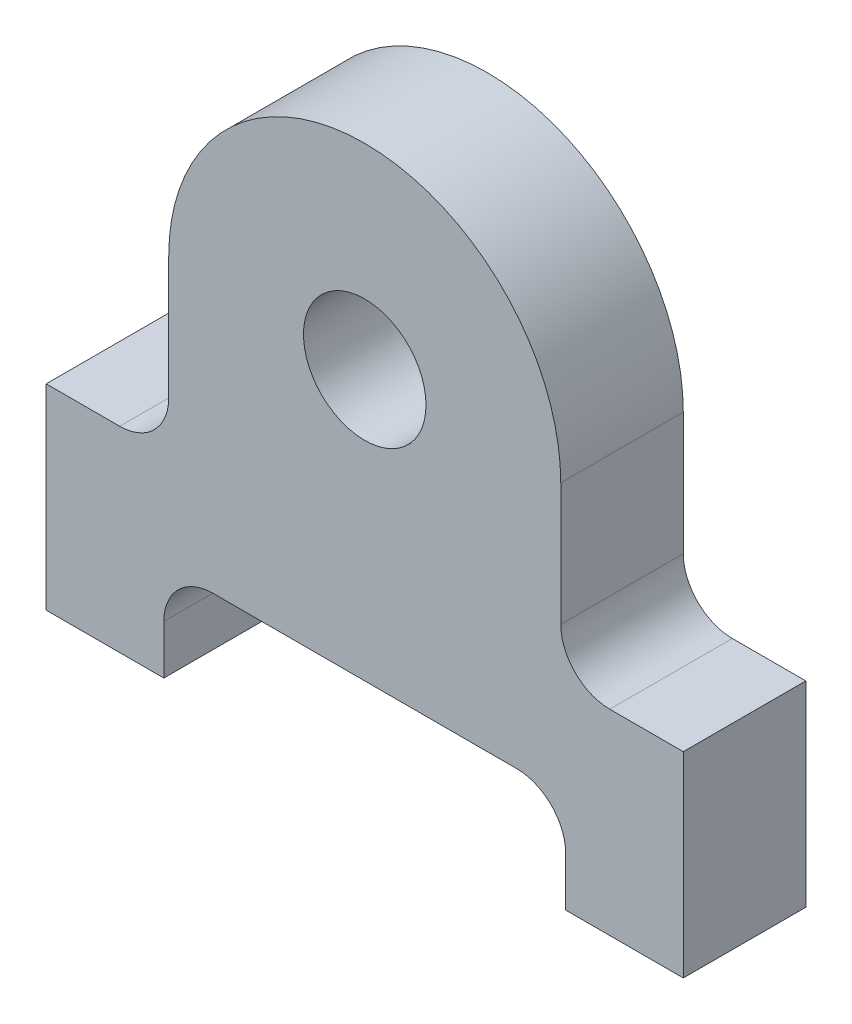
SolidWorks part; units mm, degrees
material "Plain Carbon Steel"
ref_plane "Front Plane" through (0, 0, 0) normal (0, 0, 1) x (1, 0, 0)
ref_plane "Top Plane" through (0, 0, 0) normal (0, 1, 0) x (1, 0, 0)
ref_plane "Right Plane" through (0, 0, 0) normal (1, 0, 0) x (0, 0, -1)
sketch "Sketch1" plane through (0, 0, 0) normal (0, 0, 1) x (1, 0, 0)
  line L1 (-16.51, 14.605) -> (16.51, 14.605)
  line L2 (-16.51, 14.605) -> (-16.51, -14.605)
  line L3 (-16.51, -14.605) -> (16.51, -14.605)
  line L4 (16.51, 14.605) -> (16.51, -14.605)
  line L5 (-16.51, 14.605) -> (16.51, -14.605) construction
  line L6 (-16.51, -14.605) -> (16.51, 14.605) construction
  point P0 (0, 0)
  dimension "D1" = 29.21
  dimension "D2" = 33.02
extrude "Boss-Extrude1" add sketch "Sketch1" along normal mid plane 6.35
sketch "Sketch2" plane through (0, 0, 3.175) normal (0, 0, 1) x (1, 0, 0)
  line L0 (16.51, 14.605) -> (-16.51, 14.605) construction
  line L2 (-16.51, -14.605) -> (16.51, -14.605) construction
  line L3 (-10.16, 4.445) -> (-10.16, -1.905)
  line L6 (-12.7, -4.445) -> (-16.51, -4.445)
  line L7 (0, -9.525) -> (0, -14.605) construction
  line L8 (-16.51, 14.605) -> (-16.51, -14.605) construction
  line L9 (-16.51, -4.445) -> (-16.51, 14.605)
  line L10 (-7.874, -9.525) -> (0, -9.525)
  line L11 (-10.414, -12.065) -> (-10.414, -14.605)
  line L12 (-10.414, -14.605) -> (0, -14.605)
  line L14 (-16.51, 14.605) -> (0, 14.605)
  line L16 (0, -9.525) -> (0, -14.605)
  arc A0 (0, 14.605) -> (-10.16, 4.445) centre (0, 4.445) ccw
  arc A2 (-10.16, -1.905) -> (-12.7, -4.445) centre (-12.7, -1.905) cw
  arc A4 (-7.874, -9.525) -> (-10.414, -12.065) centre (-7.874, -12.065) ccw
  point P21 (-10.16, -4.445)
  dimension "D1" = 20.32
  dimension "D5" = 5.08
extrude "Cut-Extrude1" cut sketch "Sketch2" against normal up to next
mirror "Mirror1" about plane through (0, 0, 0) normal (1, 0, 0) of "Cut-Extrude1"
sketch "Sketch3" plane through (0, 0, 3.175) normal (0, 0, 1) x (1, 0, 0)
  circle A0 centre (0, 4.445) radius 3.175
extrude "Cut-Extrude2" cut sketch "Sketch3" against normal up to next
hole_wizard "#6-32 Tapped Hole1" positions "Sketch5" profile "Sketch4" tap size "#6-32" standard "ANSI Inch"
sketch "Sketch5" plane through (0, -14.605, 0) normal (0, -1, 0) x (-1, 0, 0)
  line L0 (16.51, 0) -> (-16.51, 0) construction
  line L1 (16.51, -3.175) -> (16.51, 3.175) construction
  line L2 (-16.51, -3.175) -> (-16.51, 3.175) construction
  line L4 (-10.414, -3.175) -> (-16.51, -3.175) construction
  line L5 (-13.462, -3.175) -> (-13.462, 3.175) construction
  line L6 (-10.414, 3.175) -> (-16.51, 3.175) construction
  line L8 (16.51, -3.175) -> (10.414, -3.175) construction
  line L9 (13.462, -3.175) -> (13.462, 3.175) construction
  line L10 (16.51, 3.175) -> (10.414, 3.175) construction
  point P25 (13.462, 0)
  point P27 (-13.462, 0)
sketch "Sketch4" plane through (13.462, -14.605, 0) normal (1, 0, 0) x (0, 0, -1)
  line L0 (0, 0) -> (0, 9.7027)
  line L1 (0, 9.7027) -> (1.3525, 8.89)
  line L2 (1.3525, 8.89) -> (1.3525, 0)
  line L5 (1.3525, 0) -> (0, 0)
  line L10 (0, 9.7027) -> (-1.3526, 8.89) construction
  line L11 (0, -6.35) -> (0, 107.95) construction
  dimension "Tap Drill Dia." = 2.7051
  dimension "Tap Drill Depth" = 8.89
  dimension "Drill Angle" = 118
cosmetic thread "Hole Thread1" parameters "D1"=7.112, "D2"=3.5052
cosmetic thread "Hole Thread2" parameters "D1"=7.112, "D2"=3.5052
